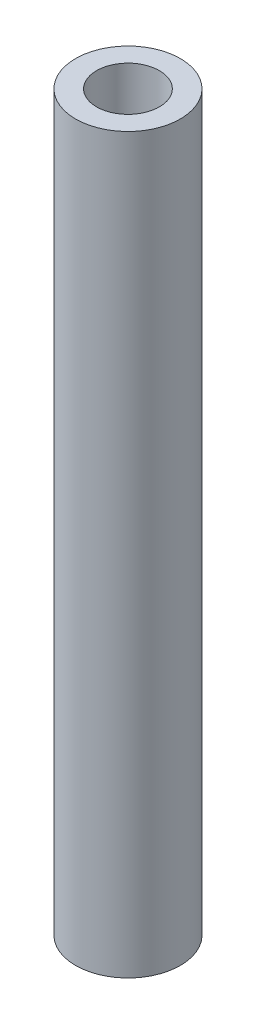
SolidWorks part; units mm, degrees
ref_plane "Front Plane" through (0, 0, 0) normal (0, 0, 1) x (1, 0, 0)
ref_plane "Top Plane" through (0, 0, 0) normal (0, 1, 0) x (1, 0, 0)
ref_plane "Right Plane" through (0, 0, 0) normal (1, 0, 0) x (0, 0, -1)
sketch "Sketch1" plane through (0, 0, 0) normal (0, 1, 0) x (1, 0, 0)
  circle A0 centre (0, 0) radius 1.5
  circle A1 centre (0, 0) radius 2.5
extrude "Boss-Extrude1" add sketch "Sketch1" along normal blind 35
